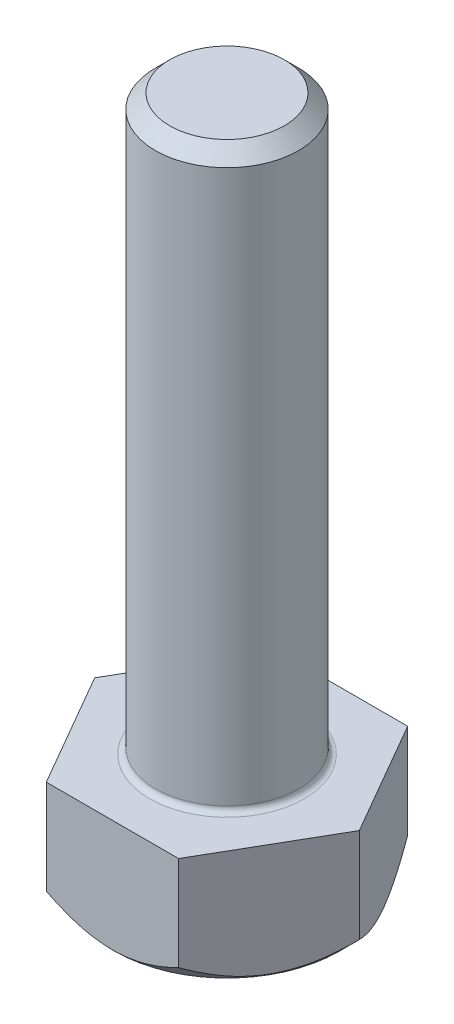
SolidWorks part; units mm, degrees
material "Cast Carbon Steel"
ref_plane "Front Plane" through (0, 0, 0) normal (0, 0, 1) x (1, 0, 0)
ref_plane "Top Plane" through (0, 0, 0) normal (0, 1, 0) x (1, 0, 0)
ref_plane "Right Plane" through (0, 0, 0) normal (1, 0, 0) x (0, 0, -1)
sketch "Sketch1" plane through (0, 0, 0) normal (0, 1, 0) x (1, 0, 0)
  line L1 (4.6188, 0) -> (2.3094, 4)
  line L2 (2.3094, 4) -> (-2.3094, 4)
  line L3 (-2.3094, 4) -> (-4.6188, 0)
  line L4 (-4.6188, 0) -> (-2.3094, -4)
  line L5 (-2.3094, -4) -> (2.3094, -4)
  line L6 (2.3094, -4) -> (4.6188, 0)
  circle A0 centre (0, 0) radius 4 construction
  dimension "D1" = 8
extrude "Boss-Extrude1" add sketch "Sketch1" along normal blind 4
sketch "Sketch2" plane through (0, 4, 0) normal (0, 1, 0) x (1, 0, 0)
  circle A0 centre (0, 0) radius 2.5
  dimension "D1" = 5
extrude "Boss-Extrude2" add sketch "Sketch2" along normal blind 20
sketch "Sketch3" plane through (0, 0, 0) normal (0, 0, 1) x (1, 0, 0)
  line L0 (0, -1000) -> (0, 49000) construction
  line L1 (-4.6188, 0.7) -> (-3.9188, 0)
  line L2 (-4.6188, 4) -> (-4.6188, 0) construction
  line L3 (-4.6188, 0) -> (-2.3094, 0) construction
  line L4 (-3.9188, 0) -> (-4.6188, 0)
  line L5 (-4.6188, 0) -> (-4.6188, 0.7)
  dimension "D1" = 45
  dimension "D2" = 0.7
revolve "Cut-Revolve1" cut sketch "Sketch3" angle 360 about L0
fillet "Fillet1" radius 0.2 1 edges at (0, 4, 2.5)
chamfer "Chamfer1" distance 0.5 angle 45 1 edges at (0, 24, 2.5)
